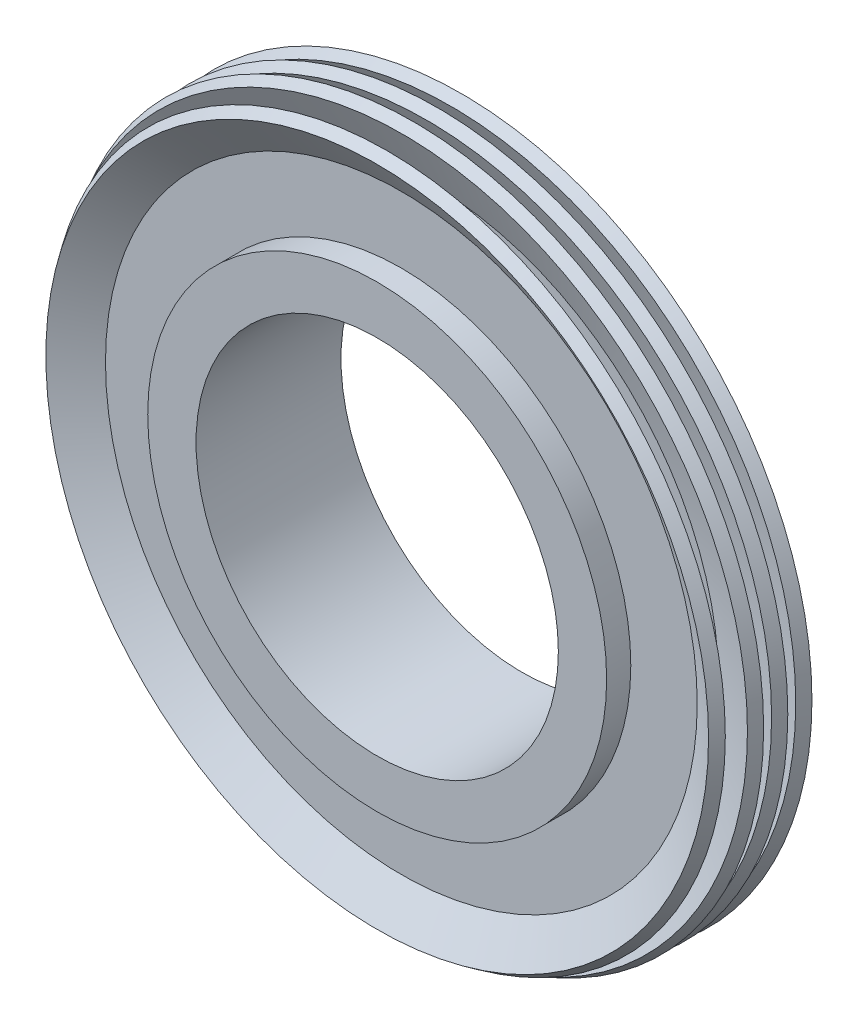
SolidWorks part; units mm, degrees
material "AISI 1020 Aço, laminado a frio"
ref_plane "Plano frontal" through (0, 0, 0) normal (0, 0, 1) x (1, 0, 0)
ref_plane "Plano superior" through (0, 0, 0) normal (0, 1, 0) x (1, 0, 0)
ref_plane "Plano direito" through (0, 0, 0) normal (1, 0, 0) x (0, 0, -1)
sketch "Esboço1" plane through (0, 0, 0) normal (0, 0, 1) x (1, 0, 0)
  circle A0 centre (0, 0) radius 15
  circle A1 centre (0, 0) radius 19
  dimension "D1" = 30
  dimension "D2" = 4
extrude "CONTRA CENTRO" add sketch "Esboço1" along normal blind 12
chamfer "Chanfro1" distance 3.5 distance2 2 1 edges at (19, 0, 0)
sketch "Esboço2" plane through (0, 0, 0) normal (1, 0, 0) x (0, 0, -1)
  line L0 (-2.5, 19) -> (-10, 19)
  line L1 (-10, 19) -> (-10, 24.5)
  line L2 (-10, 24.5) -> (-12, 27.4372)
  line L3 (-2.5, 19) -> (-2.5, 24)
  line L4 (-2.5, 24) -> (-5, 29)
  line L5 (-12, 27.4372) -> (-12, 29) construction
  line L6 (-4.5, 20) -> (-4.5, 24)
  line L7 (-4.5, 24) -> (-7, 29)
  line L8 (-7.8944, 28.5528) -> (-7, 29)
  line L9 (-9, 24.8081) -> (-11.1734, 28)
  line L10 (-9, 20) -> (-9, 24.8081)
  line L11 (-3.5, 20) -> (-4.5, 20)
  line L12 (-3.5, 20) -> (-3.5, 23.7639)
  line L13 (-3.5, 23.7639) -> (-5.8944, 28.5528)
  line L14 (-12, 27.4372) -> (-11.1734, 28)
  line L15 (-5.8944, 28.5528) -> (-5, 29)
  line L16 (-10, 19) -> (-10, 0) construction
  line L17 (-10, 0) -> (0, 0) construction
  line L18 (0, -15.5) -> (0, 15.5) construction
  line L19 (-5, 29) -> (-12, 29) construction
  line L20 (-5.5, 23.7639) -> (-7.8944, 28.5528)
  line L21 (-5.5, 20) -> (-5.5, 23.7639)
  line L22 (-6.5, 20) -> (-6.5, 24)
  line L23 (-6.5, 24) -> (-9, 29)
  line L24 (-9.8944, 28.5528) -> (-9, 29)
  line L25 (-7.5, 23.7639) -> (-9.8944, 28.5528)
  line L26 (-7.5, 20) -> (-7.5, 23.7639)
  line L27 (-7.5, 20) -> (-9, 20)
  line L28 (-5.5, 20) -> (-6.5, 20)
  line L29 (-3.5, 20) -> (-9, 20) construction
  line L30 (-3.5, 20) -> (-9, 20) construction
  line L31 (-2.5, 24) -> (-6.5, 24) construction
  line L32 (-7.5, 23.7639) -> (-3.5, 23.7639) construction
  dimension "D1" = 49
  dimension "D3" = 10
  dimension "D4" = 2.5
  dimension "D5" = 48
  dimension "D6" = 58
  dimension "D7" = 56
  dimension "D8" = 5
  dimension "D9" = 12
  dimension "D10" = 38
  dimension "D12" = 1
  dimension "D2" = 1
  dimension "D11" = 3
revolve "AA26234" add sketch "Esboço2" angle 360 about L17
